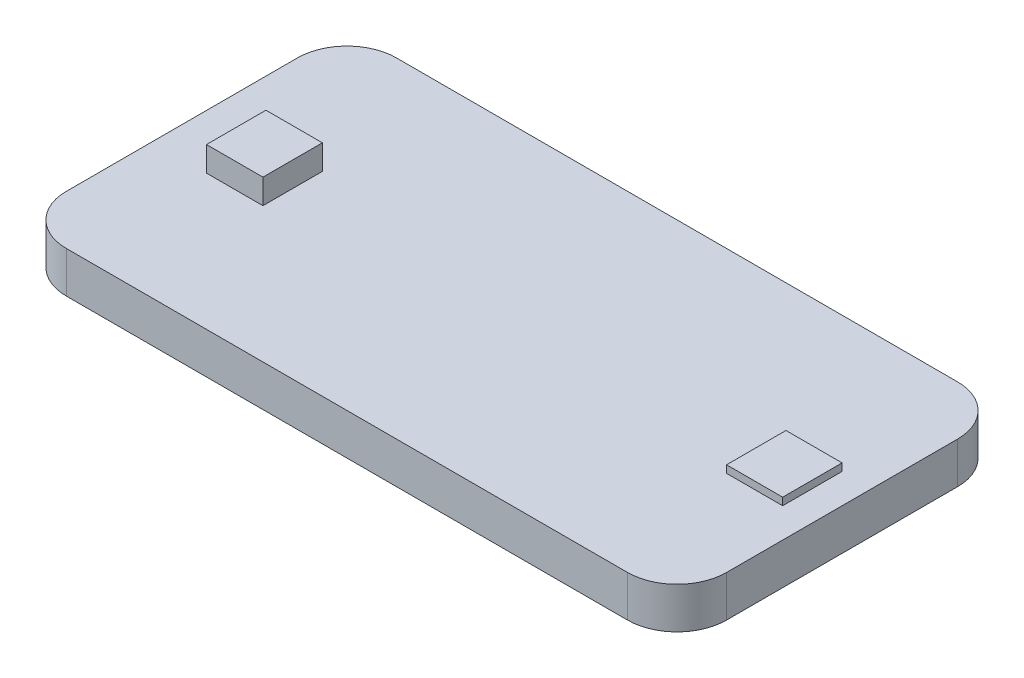
SolidWorks part; units mm, degrees
ref_plane "Front Plane" through (0, 0, 0) normal (0, 0, 1) x (1, 0, 0)
ref_plane "Top Plane" through (0, 0, 0) normal (0, 1, 0) x (1, 0, 0)
ref_plane "Right Plane" through (0, 0, 0) normal (1, 0, 0) x (0, 0, -1)
sketch "Sketch1" plane through (0, 0, 0) normal (0, 1, 0) x (1, 0, 0)
  line L1 (-400, 200) -> (400, 200)
  line L2 (-400, 200) -> (-400, -200)
  line L3 (-400, -200) -> (400, -200)
  line L4 (400, 200) -> (400, -200)
  line L5 (-400, 200) -> (400, -200) construction
  line L6 (-400, -200) -> (400, 200) construction
  point P0 (0, 0)
  dimension "D1" = 800
  dimension "D2" = 400
extrude "Boss-Extrude1" add sketch "Sketch1" along normal blind 50
fillet "Fillet1" radius 60 4 edges at (-400, 25, 200) (-400, 25, -200) (400, 25, -200) (400, 25, 200)
sketch "Sketch3" plane through (0, 50, 0) normal (0, 1, 0) x (1, 0, 0)
  line L1 (-334.2029, 36.0209) -> (-265.7971, 36.0209)
  line L2 (-334.2029, 36.0209) -> (-334.2029, -36.0209)
  line L3 (-334.2029, -36.0209) -> (-265.7971, -36.0209)
  line L4 (-265.7971, 36.0209) -> (-265.7971, -36.0209)
  line L5 (-334.2029, 36.0209) -> (-265.7971, -36.0209) construction
  line L6 (-334.2029, -36.0209) -> (-265.7971, 36.0209) construction
  point P0 (-300, 0)
extrude "Boss-Extrude2" add sketch "Sketch3" along normal up to surface (30 mm away)
sketch "Sketch5" plane through (0, 50, 0) normal (0, 1, 0) x (1, 0, 0)
  line L0 (400, -140) -> (400, 140) construction
  line L1 (296, 36) -> (364, 36)
  line L2 (296, 36) -> (296, -36)
  line L3 (296, -36) -> (364, -36)
  line L4 (364, 36) -> (364, -36)
  line L5 (296, 36) -> (364, -36) construction
  line L6 (296, -36) -> (364, 36) construction
  point P0 (330, 0)
  dimension "D1" = 68
  dimension "D2" = 72
  dimension "D3" = 70
extrude "Boss-Extrude3" add sketch "Sketch5" along normal blind 9
